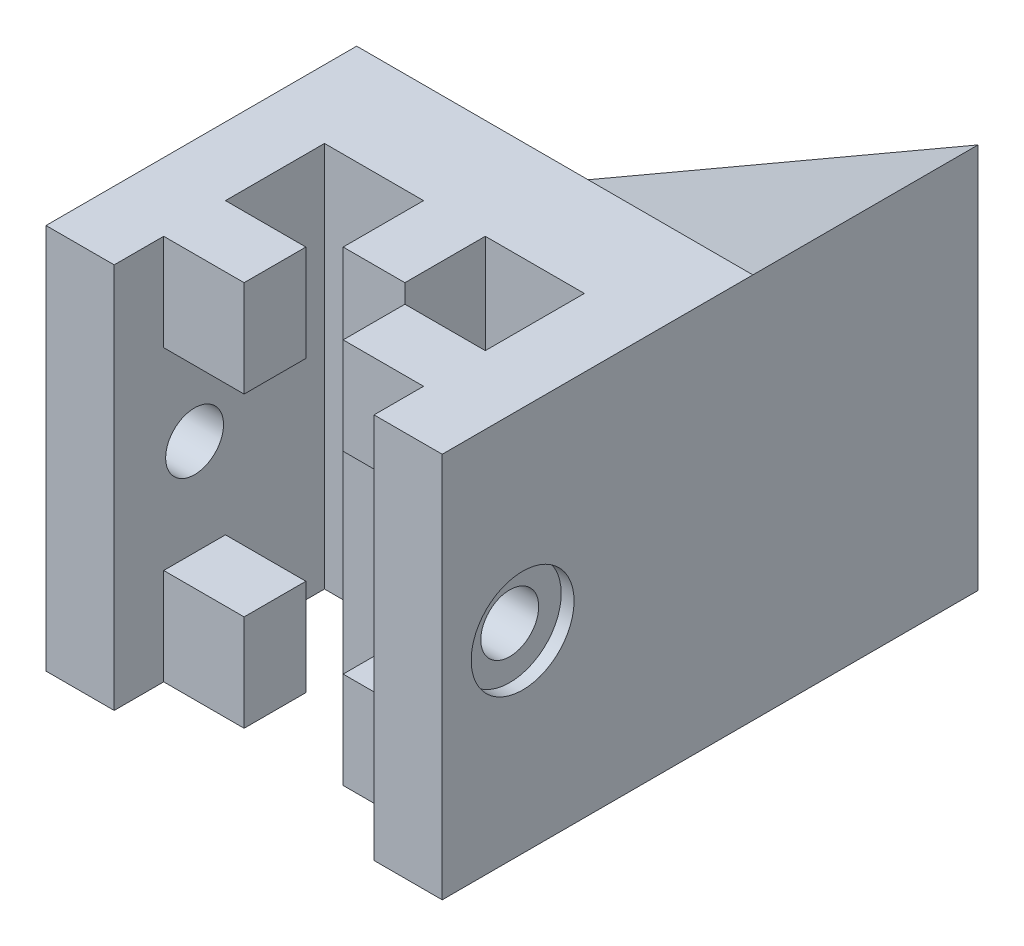
SolidWorks part; units mm, degrees
ref_plane "Plan de face" through (0, 0, 0) normal (0, 0, 1) x (1, 0, 0)
ref_plane "Plan de dessus" through (0, 0, 0) normal (0, 1, 0) x (1, 0, 0)
ref_plane "Plan de droite" through (0, 0, 0) normal (1, 0, 0) x (0, 0, -1)
sketch "Base" plane through (0, 0, 0) normal (0, 1, 0) x (1, 0, 0)
  line L0 (-3.85, -2.4) -> (-3.85, 2.4)
  line L1 (-3.85, 2.4) -> (-10.1, 2.4)
  line L2 (-10.1, 2.4) -> (-10.1, 10.1)
  line L3 (-10.1, 10.1) -> (-2.4, 10.1)
  line L4 (-2.4, 10.1) -> (-2.4, 3.85)
  line L5 (-2.4, 3.85) -> (2.4, 3.85)
  line L6 (0, -55) -> (0, 55) construction
  line L7 (2.4, 10.1) -> (2.4, 3.85)
  line L8 (10.1, 10.1) -> (2.4, 10.1)
  line L9 (10.1, 2.4) -> (10.1, 10.1)
  line L10 (3.85, 2.4) -> (10.1, 2.4)
  line L11 (3.85, -2.4) -> (3.85, 2.4)
  line L12 (-55, 0) -> (55, 0) construction
  line L13 (3.85, -2.4) -> (10.1, -2.4)
  line L14 (10.1, -2.4) -> (10.1, -6.25)
  line L20 (-10.1, -2.4) -> (-10.1, -6.25)
  line L21 (-3.85, -2.4) -> (-10.1, -2.4)
  line L23 (-15.4, 15.4) -> (15.4, 15.4)
  line L24 (-15.4, 15.4) -> (-15.4, -6.25)
  line L26 (15.4, 15.4) -> (15.4, -6.25)
  line L27 (-15.4, 15.4) -> (0, 0) construction
  line L28 (0, 0) -> (15.4, 15.4) construction
  line L29 (-10.1, -6.25) -> (-15.4, -6.25)
  line L30 (10.1, -6.25) -> (15.4, -6.25)
  line L31 (10.1, -10.1) -> (15.4, -15.4) construction
  point P2 (-3.85, 0)
  point P3 (0, 3.85)
  point P27 (0, 0)
  dimension "D1" = 4.8
  dimension "D2" = 4.8
  dimension "D3" = 6.25
  dimension "D4" = 7.7
  dimension "D5" = 30.8
extrude "Boss.-Extru.1" add sketch "Base" along normal mid plane 30
sketch "Esquisse2" plane through (0, 0, -15.4) normal (0, 0, -1) x (-1, 0, 0)
  line L0 (-15.4, 15) -> (15.4, 15)
  line L1 (15.4, 15) -> (15.4, -15)
  line L2 (15.4, -15) -> (-15.4, -15)
  line L3 (-15.4, -15) -> (-15.4, 15)
extrude "Boss.-Extru.2" add sketch "Esquisse2" along normal blind 20
sketch "Esquisse3" plane through (0, 0, -35.4) normal (0, 0, -1) x (-1, 0, 0)
  line L0 (-15.4, 15) -> (15.4, -2.7824)
  line L1 (15.4, -15) -> (15.4, 15) construction
  line L5 (-15.4, 15) -> (-15.4, -15) construction
  dimension "D1" = 60
extrude "Enlèv. mat.-Extru.2" cut sketch "Esquisse3" against normal blind 17.5 and the other way through all
sketch "Esquisse4" plane through (3.85, 0, 0) normal (-1, 0, 0) x (0, 0, 1)
  line L0 (-2.4, 15) -> (-2.4, -15) construction
  line L1 (-2.4, -7.5) -> (2.4, -7.5)
  line L2 (-2.4, -7.5) -> (-2.4, 7.5)
  line L3 (-2.4, 7.5) -> (2.4, 7.5)
  line L4 (2.4, -7.5) -> (2.4, 7.5)
  line L5 (2.4, 15) -> (2.4, -15) construction
  line L8 (-2.4, -15) -> (2.4, -15) construction
  dimension "D1" = 15
  dimension "D2" = 7.5
extrude "Enlèv. mat.-Extru.3" cut sketch "Esquisse4" against normal blind 6.25
sketch "Esquisse5" plane through (-3.85, 0, 0) normal (1, 0, 0) x (0, 0, -1)
  line L0 (-2.4, 15) -> (-2.4, -15) construction
  line L1 (-2.4, -7.5) -> (2.4, -7.5)
  line L2 (-2.4, -7.5) -> (-2.4, 7.5)
  line L3 (-2.4, 7.5) -> (2.4, 7.5)
  line L4 (2.4, -7.5) -> (2.4, 7.5)
  line L5 (2.4, 15) -> (2.4, -15) construction
  line L6 (-2.4, -15) -> (2.4, -15) construction
  dimension "D1" = 15
  dimension "D2" = 7.5
extrude "Enlèv. mat.-Extru.4" cut sketch "Esquisse5" against normal blind 6.25
hole_wizard "Chambrage pour vis à six pans creux M41" positions "Esquisse8" profile "Esquisse9" counterbore size "M4" standard "ISO"
sketch "Esquisse8" plane through (15.4, 0, 0) normal (1, 0, 0) x (0, 0, -1)
  line L0 (-6.25, 15) -> (-6.25, -15) construction
  line L1 (-6.25, 15) -> (17.9, 15) construction
  point P0 (0, 0)
  dimension "D1" = 6.25
  dimension "D2" = 15
sketch "Esquisse9" plane through (15.4, 0, 0) normal (0, 1, 0) x (0, 0, -1)
  line L0 (0, 0) -> (0, 5.3)
  line L1 (0, 5.3) -> (2.25, 5.3)
  line L3 (2.25, 5.3) -> (2.25, 1)
  line L4 (2.25, 1) -> (4, 1)
  line L5 (4, 1) -> (4, 0)
  line L7 (4, 0) -> (0, 0)
  line L11 (0, -6.35) -> (0, 107.95) construction
  dimension "Diamètre du perçage jusqu'au prochain" = 4.5
  dimension "Profondeur du perçage jusqu'au prochain" = 5.3
  dimension "Diamètre du chambrage" = 8
  dimension "Profondeur du chambrage" = 1
hole_wizard "Chambrage pour vis à six pans creux M43" positions "Esquisse12" profile "Esquisse13" counterbore size "M4" standard "ISO" end condition up to next
sketch "Esquisse12" plane through (-15.4, 0, 0) normal (-1, 0, 0) x (0, 0, 1)
  line L0 (-17.9, 15) -> (6.25, 15) construction
  line L1 (6.25, 15) -> (6.25, -15) construction
  point P0 (0, 0)
  point P9 (-3.2717, 1.2507)
  point P10 (0, 0)
  dimension "D1" = 15
  dimension "D2" = 6.25
sketch "Esquisse13" plane through (-15.4, 0, 0) normal (0, 1, 0) x (0, 0, 1)
  line L0 (0, 0) -> (0, 5.3)
  line L1 (0, 5.3) -> (2.25, 5.3)
  line L3 (2.25, 5.3) -> (2.25, 1)
  line L4 (2.25, 1) -> (4, 1)
  line L5 (4, 1) -> (4, 0)
  line L7 (4, 0) -> (0, 0)
  line L11 (0, -6.35) -> (0, 107.95) construction
  dimension "Diamètre du perçage jusqu'au prochain" = 4.5
  dimension "Profondeur du perçage jusqu'au prochain" = 5.3
  dimension "Diamètre du chambrage" = 8
  dimension "Profondeur du chambrage" = 1
